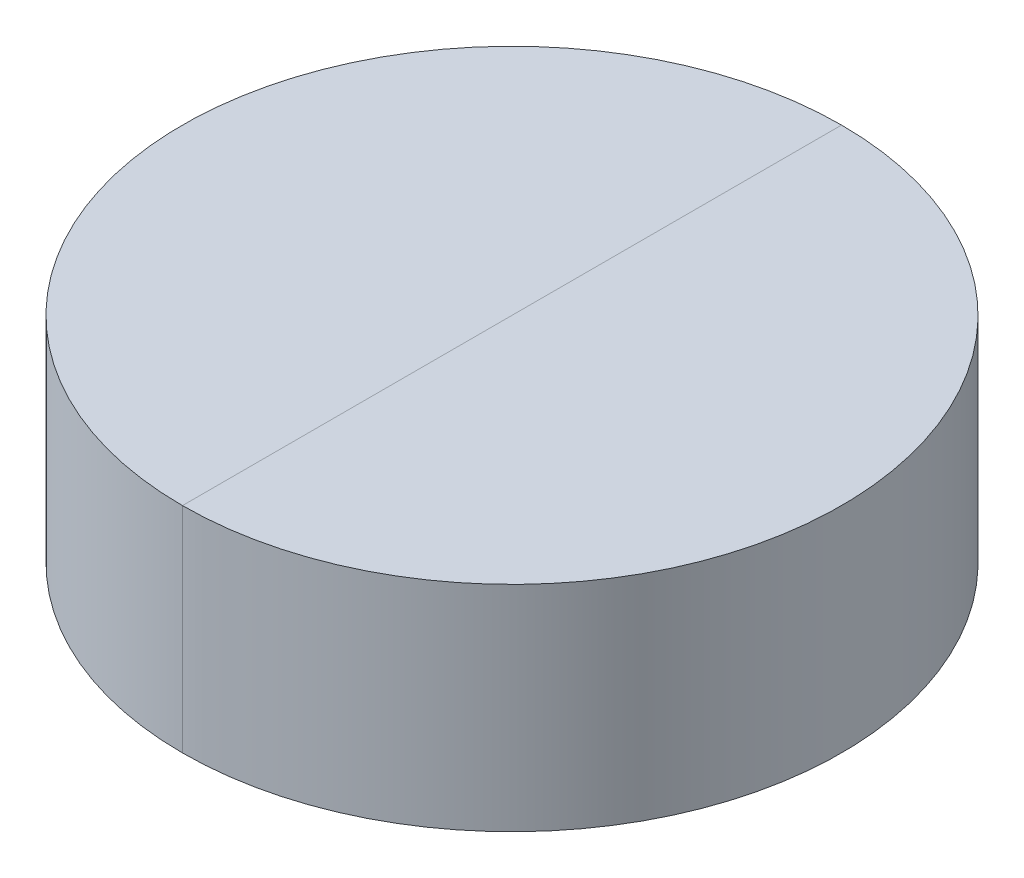
SolidWorks part; units mm, degrees
ref_plane "Plan de face" through (0, 0, 0) normal (0, 0, 1) x (1, 0, 0)
ref_plane "Plan de dessus" through (0, 0, 0) normal (0, 1, 0) x (1, 0, 0)
ref_plane "Plan de droite" through (0, 0, 0) normal (1, 0, 0) x (0, 0, -1)
sketch "Esquisse1" plane through (0, 0, 0) normal (0, 1, 0) x (1, 0, 0)
  line L0 (0, 4) -> (0, -4)
  arc A0 (0, 4) -> (0, -4) centre (0, 0) ccw
  dimension "D1" = 8
extrude "Boss.-Extru.1" add sketch "Esquisse1" along normal blind 2.6
sketch "Esquisse2" plane through (0, 0, 0) normal (0, 1, 0) x (1, 0, 0)
  line L0 (0, -4) -> (0, 4)
  arc A0 (0, -4) -> (0, 4) centre (0, 0) ccw
extrude "Boss.-Extru.2" add sketch "Esquisse2" along normal up to surface (2.6 mm away) separate body up to face at (-2, 2.6, 0)
